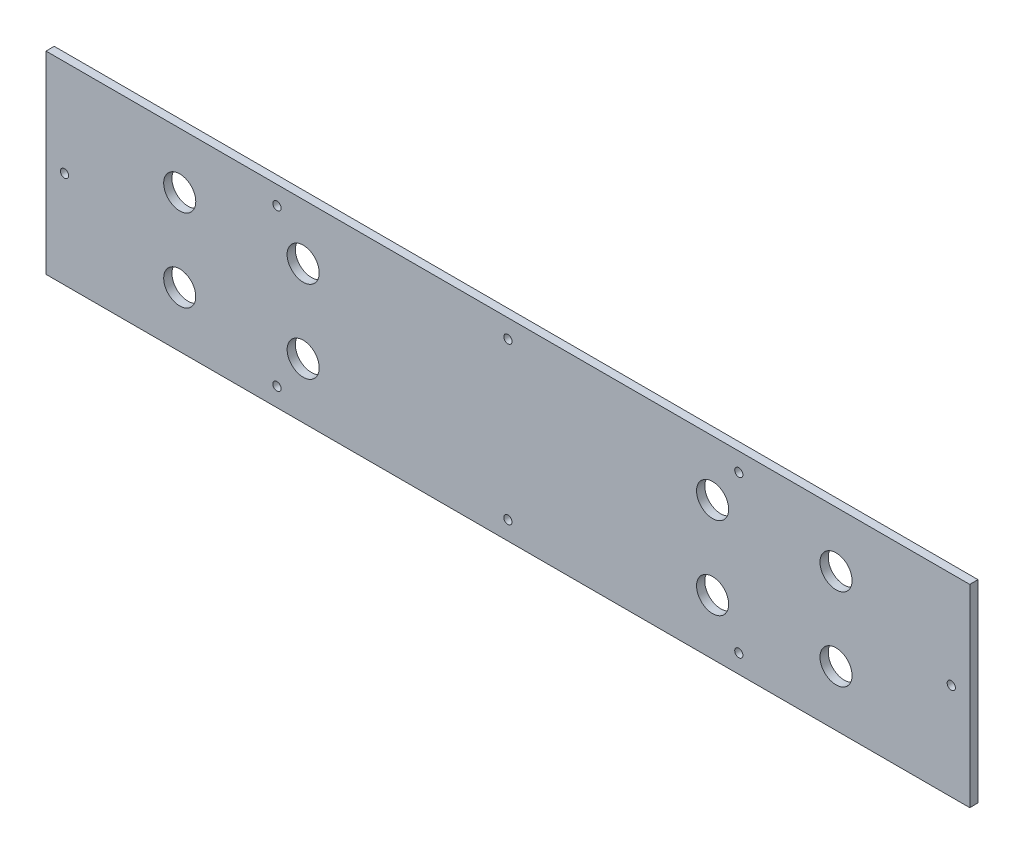
SolidWorks part; units mm, degrees
ref_plane "Piano frontale" through (0, 0, 0) normal (0, 0, 1) x (1, 0, 0)
ref_plane "Piano superiore" through (0, 0, 0) normal (0, 1, 0) x (1, 0, 0)
ref_plane "Piano destro" through (0, 0, 0) normal (1, 0, 0) x (0, 0, -1)
sketch "Schizzo1" plane through (0, 0, 0) normal (0, 0, 1) x (1, 0, 0)
  line L0 (-224.5, 351.6275) -> (-224.5, -66.2585) construction
  line L1 (0, 0) -> (-449, 0)
  line L2 (0, 0) -> (0, 94)
  line L3 (0, 94) -> (-449, 94)
  line L4 (-449, 0) -> (-449, 94)
  line L5 (-384, 47) -> (120.8821, 47) construction
  line L6 (-476.1211, 67) -> (22.7405, 67) construction
  line L7 (-476.1211, 27) -> (22.7405, 27) construction
  line L8 (-354, 67) -> (-354, 27) construction
  line L9 (-224.5, 94) -> (-449, 0) construction
  line L10 (-336.75, 47) -> (-336.75, 0) construction
  line L11 (-95, 67) -> (-95, 27) construction
  circle A0 centre (-384, 27) radius 7.8
  circle A1 centre (-9, 47) radius 2
  circle A2 centre (-224.5, 85) radius 2
  circle A3 centre (-440, 47) radius 2
  circle A4 centre (-224.5, 9) radius 2
  circle A5 centre (-324, 27) radius 7.8
  circle A6 centre (-324, 67) radius 7.8
  circle A7 centre (-336.75, 85) radius 2
  circle A8 centre (-384, 67) radius 7.8
  circle A9 centre (-336.75, 9) radius 2
  circle A10 centre (-112.25, 9) radius 2
  circle A11 centre (-112.25, 85) radius 2
  circle A12 centre (-65, 67) radius 7.8
  circle A13 centre (-65, 27) radius 7.8
  circle A14 centre (-125, 27) radius 7.8
  circle A15 centre (-125, 67) radius 7.8
  point P9 (-224.5, 47)
  dimension "D3" = 4
  dimension "D2" = 4
  dimension "D5" = 65
  dimension "D8" = 4
  dimension "D9" = 9
  dimension "D10" = 15.6
  dimension "D12" = 15.6
  dimension "D14" = 15.6
  dimension "D1" = 449
  dimension "314" = 94
  dimension "D4" = 9
  dimension "D6" = 9
  dimension "D7" = 30
  dimension "D11" = 20
  dimension "D13" = 65
  dimension "D15" = 95
  dimension "D16" = 95
extrude "Estrusione-Estrusione1" add sketch "Schizzo1" along normal blind 4
